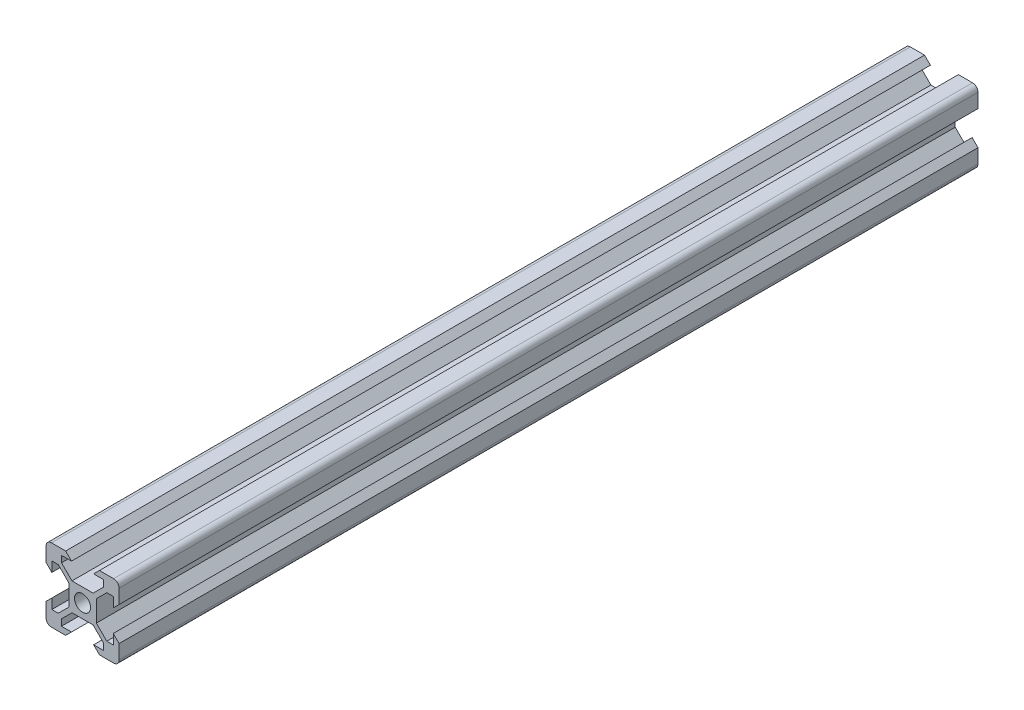
SolidWorks part; units mm, degrees
ref_plane "Front Plane" through (0, 0, 0) normal (0, 0, 1) x (1, 0, 0)
ref_plane "Top Plane" through (0, 0, 0) normal (0, 1, 0) x (1, 0, 0)
ref_plane "Right Plane" through (0, 0, 0) normal (1, 0, 0) x (0, 0, -1)
sketch "Sketch1" plane through (0, 0, 0) normal (0, 0, 1) x (1, 0, 0)
  line L0 (-5.7847, 7.544) -> (-11.512, 13.2713)
  line L1 (-7.544, 7.544) -> (7.544, 7.544)
  line L2 (-7.544, 7.544) -> (-7.544, -7.544)
  line L3 (-7.544, -7.544) -> (7.544, -7.544)
  line L4 (7.544, 7.544) -> (7.544, -7.544)
  line L5 (-7.544, 7.544) -> (7.544, -7.544) construction
  line L6 (-7.544, -7.544) -> (7.544, 7.544) construction
  line L7 (-11.512, 13.2713) -> (-11.512, 16.8)
  line L8 (-11.512, 16.8) -> (-6.052, 16.8)
  line L9 (-6.052, 16.8) -> (-9.252, 20)
  line L10 (-9.252, 20) -> (-17, 20)
  line L11 (-20, 17) -> (-20, 9.252)
  line L12 (-20, 9.252) -> (-16.8, 6.052)
  line L13 (-16.8, 6.052) -> (-16.8, 11.512)
  line L14 (-16.8, 11.512) -> (-13.2713, 11.512)
  line L15 (-13.2713, 11.512) -> (-7.544, 5.7847)
  line L16 (-19.1213, 19.1213) -> (0, 0) construction
  line L17 (13.2713, 11.512) -> (16.8, 11.512)
  line L18 (20, 9.252) -> (20, 17)
  line L19 (17, 20) -> (9.252, 20)
  line L20 (9.252, 20) -> (6.052, 16.8)
  line L21 (6.052, 16.8) -> (11.512, 16.8)
  line L22 (11.512, 16.8) -> (11.512, 13.2713)
  line L23 (11.512, 13.2713) -> (5.7847, 7.544)
  line L24 (7.544, 5.7847) -> (13.2713, 11.512)
  line L25 (16.8, 11.512) -> (16.8, 6.052)
  line L26 (16.8, 6.052) -> (20, 9.252)
  line L27 (19.1213, 19.1213) -> (0, 0) construction
  line L28 (11.512, -13.2713) -> (11.512, -16.8)
  line L29 (9.252, -20) -> (17, -20)
  line L30 (20, -17) -> (20, -9.252)
  line L31 (20, -9.252) -> (16.8, -6.052)
  line L32 (16.8, -6.052) -> (16.8, -11.512)
  line L33 (16.8, -11.512) -> (13.2713, -11.512)
  line L34 (13.2713, -11.512) -> (7.544, -5.7847)
  line L35 (5.7847, -7.544) -> (11.512, -13.2713)
  line L36 (11.512, -16.8) -> (6.052, -16.8)
  line L37 (6.052, -16.8) -> (9.252, -20)
  line L38 (19.1213, -19.1213) -> (0, 0) construction
  line L39 (-13.2713, -11.512) -> (-16.8, -11.512)
  line L40 (-20, -9.252) -> (-20, -17)
  line L41 (-17, -20) -> (-9.252, -20)
  line L42 (-9.252, -20) -> (-6.052, -16.8)
  line L43 (-6.052, -16.8) -> (-11.512, -16.8)
  line L44 (-11.512, -16.8) -> (-11.512, -13.2713)
  line L45 (-11.512, -13.2713) -> (-5.7847, -7.544)
  line L46 (-7.544, -5.7847) -> (-13.2713, -11.512)
  line L47 (-16.8, -11.512) -> (-16.8, -6.052)
  line L48 (-16.8, -6.052) -> (-20, -9.252)
  line L49 (-19.1213, -19.1213) -> (0, 0) construction
  circle A0 centre (0, 0) radius 4.4
  arc A1 (-17, 20) -> (-20, 17) centre (-17, 17) ccw
  arc A2 (20, 17) -> (17, 20) centre (17, 17) ccw
  arc A3 (17, -20) -> (20, -17) centre (17, -17) ccw
  arc A4 (-20, -17) -> (-17, -20) centre (-17, -17) ccw
  point P66 (0, 0)
  dimension "D1" = 8.8
  dimension "D8" = 3
  dimension "D2" = 15.088
  dimension "D3" = 2.488
  dimension "D4" = 8.488
  dimension "D5" = 3.2
  dimension "D6" = 20
  dimension "D7" = 15.2
  dimension "D9" = 4
extrude "Boss-Extrude1" add sketch "Sketch1" along normal mid plane 470 contours L10 A1 L11 L12 L13 L14 L15 L2 L1 L0 L7 L8 L9 | L18 A2 L19 L20 L21 L22 L23 L1 L4 L24 L17 L25 L26 | L40 A4 L41 L42 L43 L44 L45 L3 L2 L46 L39 L47 L48 | L29 A3 L30 L31 L32 L33 L34 L4 L3 L35 L28 L36 L37 | L4 L1 L2 L3 A0
equation "\"longitud\"= 800"
